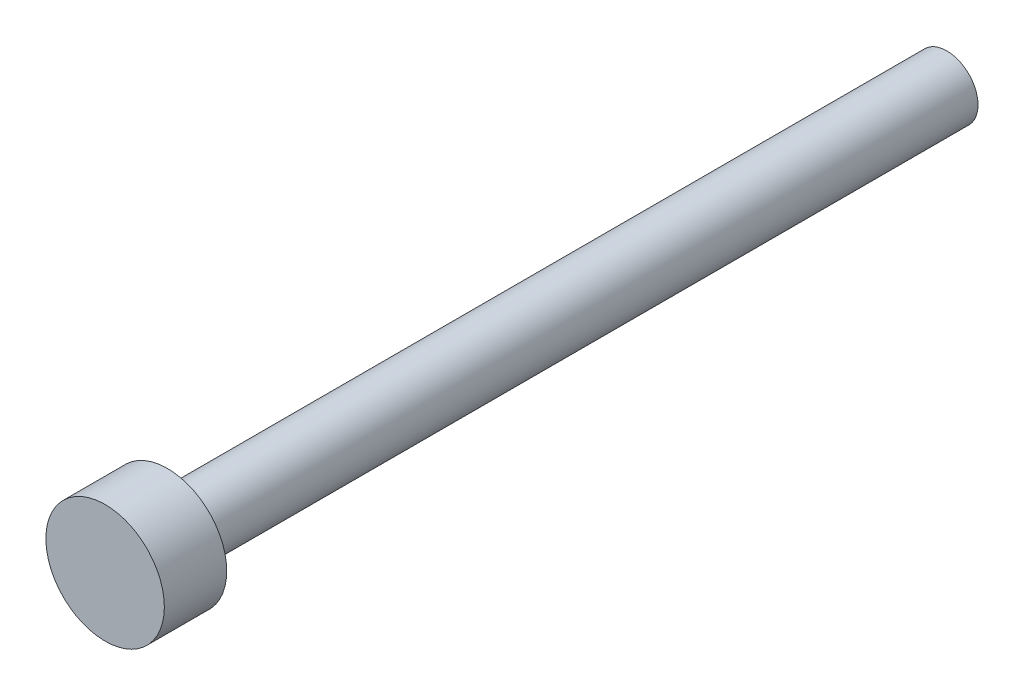
SolidWorks part; units mm, degrees
ref_plane "Front Plane" through (0, 0, 0) normal (0, 0, 1) x (1, 0, 0)
ref_plane "Top Plane" through (0, 0, 0) normal (0, 1, 0) x (1, 0, 0)
ref_plane "Right Plane" through (0, 0, 0) normal (1, 0, 0) x (0, 0, -1)
sketch "Shank_nominal_thread_envelope_profile" plane through (0, 0, 0) normal (0, 0, 1) x (1, 0, 0)
  circle A0 centre (0, 0) radius 1
  dimension "D1" = 2
extrude "Shank_nominal_thread_envelope" add sketch "Shank_nominal_thread_envelope_profile" along normal blind 25 from offset 25
sketch "Socket_head_envelope_profile" plane through (0, 0, 0) normal (0, 0, 1) x (1, 0, 0)
  circle A0 centre (0, 0) radius 1.9
  dimension "D1" = 3.8
extrude "Socket_head_envelope" add sketch "Socket_head_envelope_profile" along normal blind 2
